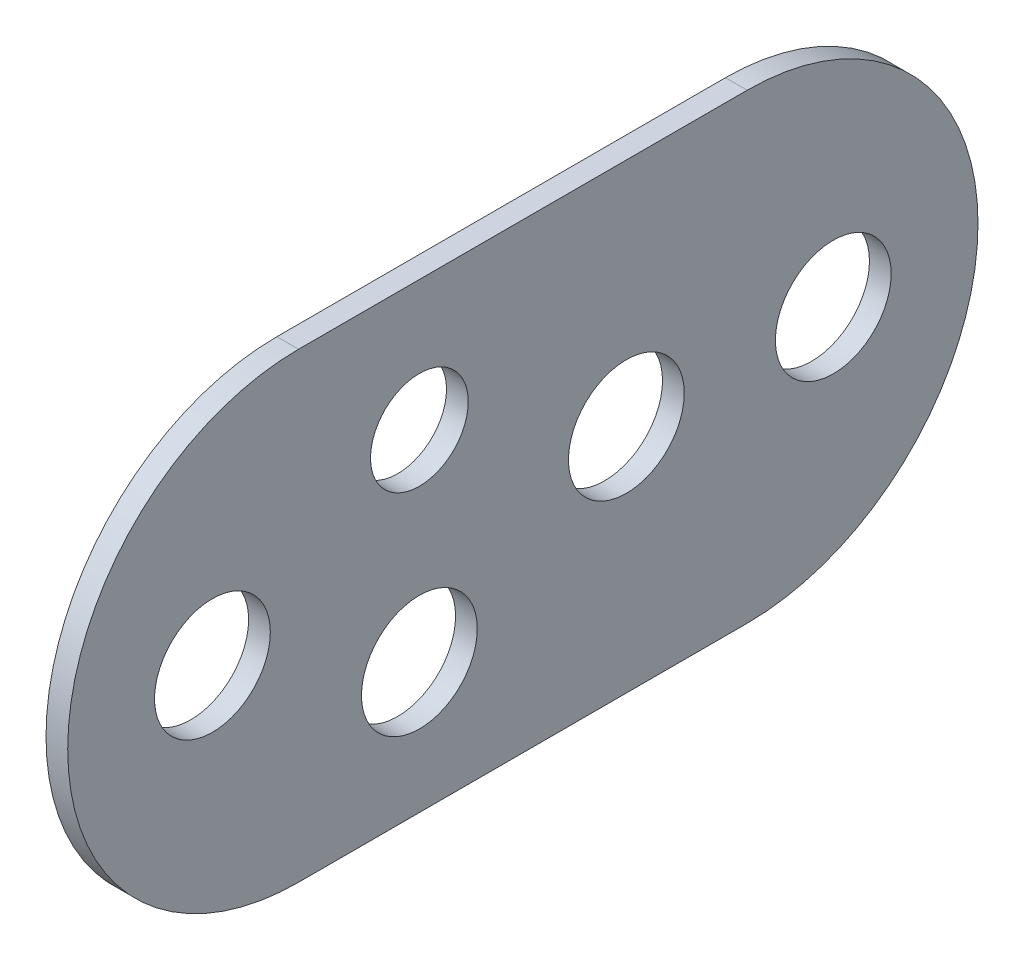
SolidWorks part; units mm, degrees
ref_plane "Front Plane" through (0, 0, 0) normal (0, 0, 1) x (1, 0, 0)
ref_plane "Top Plane" through (0, 0, 0) normal (0, 1, 0) x (1, 0, 0)
ref_plane "Right Plane" through (0, 0, 0) normal (1, 0, 0) x (0, 0, -1)
sketch "Sketch1" plane through (0, 0, 0) normal (1, 0, 0) x (0, 0, -1)
  line L0 (-31, 0) -> (31, 0) construction
  line L1 (-31, 32) -> (31, 32) construction
  line L2 (-31, -32) -> (31, -32) construction
  line L3 (-31, 31.9) -> (31, 31.9)
  line L4 (-31, -31.9) -> (31, -31.9)
  arc A0 (-31, 32) -> (-31, -32) centre (-31, 0) ccw construction
  arc A1 (31, -32) -> (31, 32) centre (31, 0) ccw construction
  arc A2 (31, -31.9) -> (31, 31.9) centre (31, 0) ccw
  arc A3 (-31, 31.9) -> (-31, -31.9) centre (-31, 0) ccw
  point P2 (0, 0)
  dimension "D1" = 64
  dimension "D2" = 62
  dimension "D3" = 0.1
extrude "Boss-Extrude1" add sketch "Sketch1" along normal mid plane 3
sketch "Sketch2" plane through (1.5, 0, 0) normal (1, 0, 0) x (0, 0, -1)
  line L0 (-42.9, 0) -> (-14.3, 0) construction
  line L1 (-14.3, 0) -> (14.3, 0) construction
  line L2 (14.3, 0) -> (42.9, 0) construction
  line L3 (-42.9, 0) -> (-62.9, 0) construction
  line L8 (-14.3, -13.9) -> (-14.3, 0) construction
  line L9 (-14.3, -21.9) -> (-14.3, -26.9) construction
  line L10 (-31, -26.9) -> (31, -26.9)
  line L11 (31, 26.9) -> (-31, 26.9)
  line L12 (-31, -26.9) -> (31, -26.9) construction
  line L13 (31, 26.9) -> (-31, 26.9) construction
  circle A0 centre (-14.3, 0) radius 8 construction
  circle A1 centre (-42.9, 0) radius 8
  circle A2 centre (42.9, 0) radius 8
  circle A3 centre (-14.3, 13.9) radius 6.75
  circle A4 centre (14.3, 0) radius 8
  arc A5 (-31, 31.9) -> (-31, -31.9) centre (-31, 0) ccw construction
  circle A6 centre (-14.3, -13.9) radius 8
  circle A8 centre (-14.3, 13.9) radius 8 construction
  arc A12 (-31, 26.9) -> (-31, -26.9) centre (-31, 0) ccw
  arc A13 (31, -26.9) -> (31, 26.9) centre (31, 0) ccw
  arc A14 (-31, 26.9) -> (-31, -26.9) centre (-31, 0) ccw construction
  arc A15 (31, -26.9) -> (31, 26.9) centre (31, 0) ccw construction
  point P2 (-50.9, 0)
  point P22 (-14.3, 31.4728)
  point P23 (-14.3, 14.2783)
  dimension "D1" = 16
  dimension "D2" = 12
  dimension "D3" = 13.5
  dimension "D4" = 5
  dimension "D5" = 5
extrude "Cut-Extrude1" cut sketch "Sketch2" against normal through all
